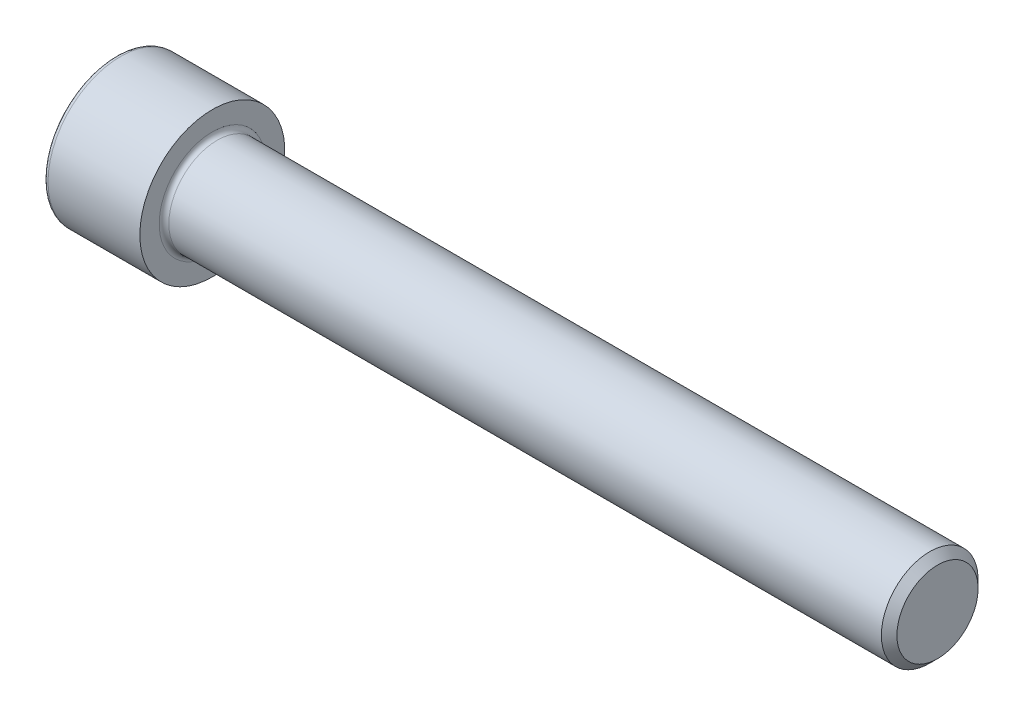
SolidWorks part; units mm, degrees
revolve "Base-Revolve" add sketch "BodySke"
sketch "BodySke" plane through (0, 0, 0) normal (0, 0, 1) x (1, 0, 0)
  line L0 (0, 0) -> (0, 9)
  line L1 (0, 9) -> (12, 9)
  line L2 (12, 9) -> (12, 6)
  line L3 (12, 6) -> (101.036, 6)
  line L4 (102, 5.036) -> (102, 0)
  line L5 (102, 0) -> (0, 0)
  line L6 (-31.75, 0) -> (127, 0) construction
  line L8 (102, 5.036) -> (101.036, 6)
  line L10 (102, -5.036) -> (101.036, -6) construction
  line L11 (13.75, 9.525) -> (13.75, 3.175) construction
  line L12 (12, 9.525) -> (12, 3.175) construction
  line L13 (42, 9.525) -> (42, 3.175) construction
  dimension "Head_ht" = 12
  dimension "Length" = 90
  dimension "Body_ch_ang" = 45
  dimension "Diameter" = 12
  dimension "Minor_dia" = 10.072
  dimension "Advance" = 1.75
  dimension "Thread_nom" = 90
  dimension "Thread_length" = 60
  dimension "Head_dia" = 18
cosmetic thread "ThreadCosmetic" [suppressed]
fillet "Fillet1" radius 0.6 1 edges at (12, 0, 6)
fillet "Fillet2" radius 0.6 1 edges at (0, 0, 9)
ref_plane "Plane1" through (0, 0, 0) normal (0, 0, 1) x (1, 0, 0)
ref_plane "Plane2" through (0, 0, 0) normal (0, 1, 0) x (1, 0, 0)
ref_plane "Plane3" through (0, 0, 0) normal (1, 0, 0) x (0, 0, -1)
sketch "Sketch2" plane through (0, 0, 0) normal (0, 0, 1) x (1, 0, 0)
  line L0 (0, 5.0575) -> (6, 5.0575)
  line L1 (6, 5.0575) -> (8.9199, 0)
  line L2 (-31.75, 0) -> (127, 0) construction
  line L3 (8.9199, 0) -> (0, 0)
  line L4 (0, 0) -> (0, 5.0575)
  line L6 (0, 0) -> (47.625, 0) construction
  dimension "D1" = 5.0575
  dimension "D2" = 60
  dimension "Depth" = 6
revolve "Hex-PreBroach" cut sketch "Sketch2" angle 360 about L6
sketch "Sketch3" plane through (0, 0, 0) normal (-1, 0, 0) x (0, 0.5, 0.866)
  line L0 (2.9199, 5.0575) -> (-2.9199, 5.0575)
  line L1 (-2.9199, 5.0575) -> (-5.8399, 0)
  line L2 (2.9199, 5.0575) -> (5.8399, 0)
  line L3 (2.9199, -5.0575) -> (5.8399, 0)
  line L4 (2.9199, -5.0575) -> (-2.9199, -5.0575)
  line L5 (-2.9199, -5.0575) -> (-5.8399, 0)
  dimension "D1" = 5.0575
  dimension "D2" = 5.0575
  dimension "Hex_size" = 10.115
extrude "Hex" cut sketch "Sketch3" against normal blind 6
sketch "ThdSchSke" plane through (0, 0, 0) normal (0, 0, 1) x (1, 0, 0)
  line L0 (17.25, -5.036) -> (16.575, -6)
  line L1 (17.25, -5.036) -> (17.925, -6)
  line L2 (17.925, -6) -> (17.925, -7.5)
  line L3 (-3.175, 0) -> (5.1513, 0) construction
  line L4 (0, 8.4) -> (0, -8.4) construction
  line L5 (17.925, -7.5) -> (16.575, -7.5)
  line L6 (16.575, -7.5) -> (16.575, -6)
  dimension "Thread_minor" = 10.072
  dimension "Diameter" = 12
  dimension "Start" = 17.25
revolve "ThreadSchematic" [suppressed] cut sketch "ThdSchSke" angle 360 about L3
pattern_linear "ThdSchPat" [suppressed]
equation "\"D2@Sketch3\" = \"Hex_size@Sketch3\" / 2"
equation "\"D1@Sketch3\" = \"Hex_size@Sketch3\" / 2"
equation "\"D1@Sketch2\" = \"Hex_size@Sketch3\" / 2"
equation "\"Thread_minor@ThreadCosmetic\"  =  \"Minor_dia@BodySke\""
equation "\"Depth@Sketch2\" =  \"Key_eng@Hex\""
equation "\"Thread_length@ThreadCosmetic\" = ((sgn( (\"Length@BodySke\" - \"Advance@BodySke\" * 3.0) - \"Thread_nom@BodySke\" )-1)*( (\"Length@BodySke\" - \"Advance@BodySke\" * 3.0) - \"Thread_nom@BodySke\" ))/-2+ \"Thread_nom@BodySke\""
equation "\"Thread_minor@ThdSchSke\" = \"Minor_dia@BodySke\""
equation "\"Diameter@ThdSchSke\" = \"Diameter@BodySke\""
equation "\"Overcut@ThdSchSke\" = \"Diameter@BodySke\" * 1.25"
equation "\"Start@ThdSchSke\" = \"Head_ht@BodySke\" + \"Length@BodySke\" - \"Thread_length@ThreadCosmetic\"  '---Non-countersunk---"
equation "\"Num_threads@ThdSchPat\" = int( \"Thread_length@ThreadCosmetic\" / \"Advance@BodySke\" + 0.999 )  + 1"
equation "\"Advance@ThdSchPat\" = \"Thread_length@ThreadCosmetic\" /  (\"Num_threads@ThdSchPat\" - 1) 'relax it"
equation "\"Num_threads@ThdSchPat\" = \"Num_threads@ThdSchPat\" - sgn( \"Num_threads@ThdSchPat\" - 1) '---chamfered tips only---"
